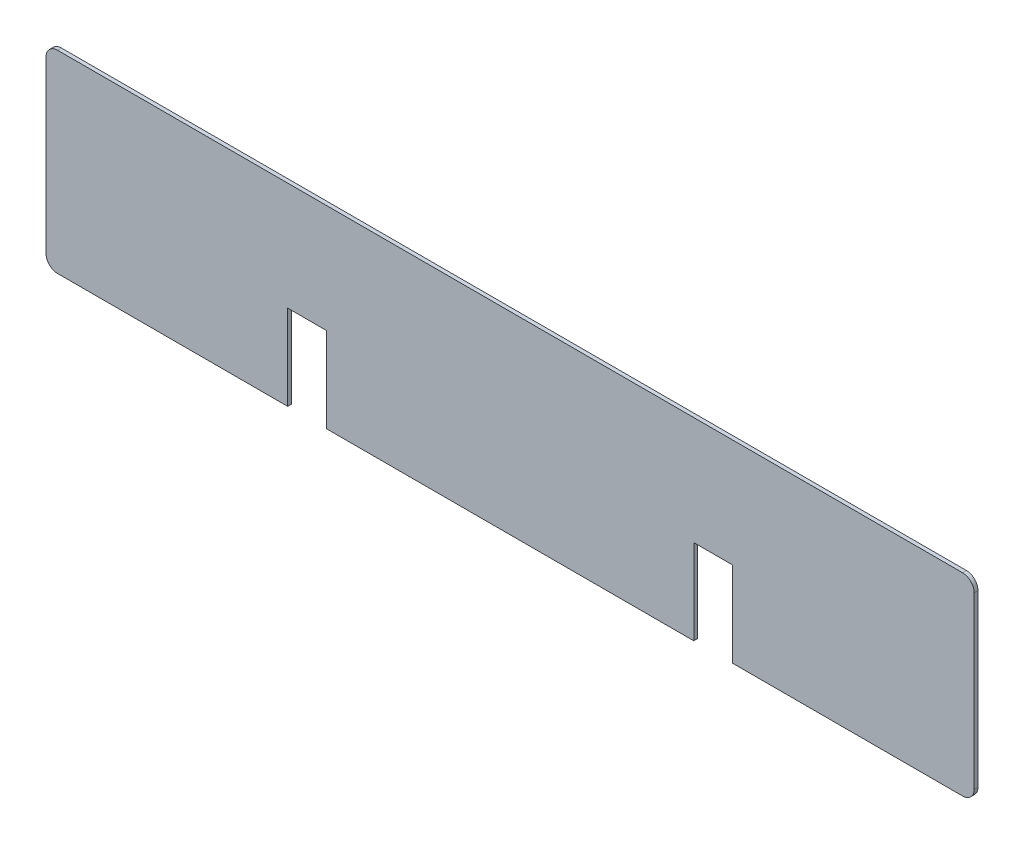
SolidWorks part; units mm, degrees
material "Thornel Mat VMA"
ref_plane "前视基准面" through (0, 0, 0) normal (0, 0, 1) x (1, 0, 0)
ref_plane "上视基准面" through (0, 0, 0) normal (0, 1, 0) x (1, 0, 0)
ref_plane "右视基准面" through (0, 0, 0) normal (1, 0, 0) x (0, 0, -1)
other "Configuration Table"
sketch "草图1" plane through (0, 0, 0) normal (0, 0, 1) x (1, 0, 0)
  line L1 (-120, 25) -> (120, 25)
  line L2 (-120, 25) -> (-120, -25)
  line L3 (-120, -25) -> (120, -25)
  line L4 (120, 25) -> (120, -25)
  line L5 (-120, 25) -> (120, -25) construction
  line L6 (-120, -25) -> (120, 25) construction
  point P0 (0, 0)
  dimension "D1" = 50
  dimension "D2" = 240
extrude "凸台-拉伸1" add sketch "草图1" along normal blind 1
fillet "圆角1" radius 3 4 edges at (120, -25, 0.5) (120, 25, 0.5) (-120, -25, 0.5) (-120, 25, 0.5)
sketch "草图2" plane through (0, 0, 1) normal (0, 0, 1) x (1, 0, 0)
  line L0 (-117, -25) -> (117, -25) construction
  line L1 (-57.5, -3) -> (-47.5, -3)
  line L2 (-57.5, -3) -> (-57.5, -25)
  line L3 (-57.5, -25) -> (-47.5, -25)
  line L4 (-47.5, -3) -> (-47.5, -25)
  line L5 (-57.5, -3) -> (-47.5, -25) construction
  line L6 (-57.5, -25) -> (-47.5, -3) construction
  line L8 (47.5, -3) -> (57.5, -3)
  line L9 (47.5, -3) -> (47.5, -25)
  line L10 (47.5, -25) -> (57.5, -25)
  line L11 (57.5, -3) -> (57.5, -25)
  line L12 (47.5, -3) -> (57.5, -25) construction
  line L13 (47.5, -25) -> (57.5, -3) construction
  point P0 (-52.5, -14)
  point P7 (52.5, -14)
  point P14 (-30.2251, -4.7083)
  dimension "D1" = 105
  dimension "D2" = 52.5
  dimension "D3" = 10
  dimension "D4" = 10
  dimension "D5" = 22
  dimension "D6" = 22
extrude "切除-拉伸1" cut sketch "草图2" against normal through all
